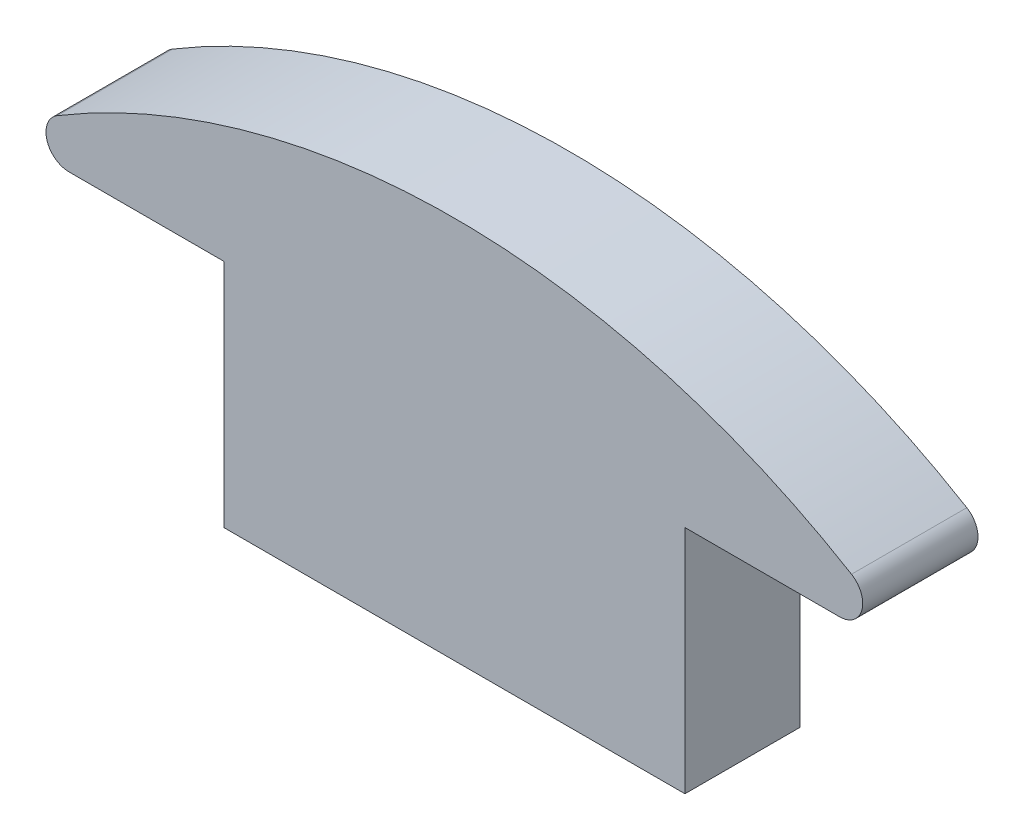
SolidWorks part; units mm, degrees
ref_plane "Ön Düzlem" through (0, 0, 0) normal (0, 0, 1) x (1, 0, 0)
ref_plane "Üst Düzlem" through (0, 0, 0) normal (0, 1, 0) x (1, 0, 0)
ref_plane "Sağ Düzlem" through (0, 0, 0) normal (1, 0, 0) x (0, 0, -1)
sketch "Sketch1" plane through (0, 0, 0) normal (0, 0, 1) x (1, 0, 0)
  line L0 (0, 1) -> (-0.671, 1)
  line L2 (0, 1) -> (0, 0)
  line L3 (0, 0) -> (2, 0)
  line L4 (2, 1) -> (2, 0)
  line L5 (2, 1) -> (2.671, 1)
  arc A0 (-0.7224, 1.1858) -> (2.7224, 1.1858) centre (1, -1.688) cw
  arc A1 (2.671, 1) -> (2.7224, 1.1858) centre (2.671, 1.1) ccw
  arc A2 (-0.671, 1) -> (-0.7224, 1.1858) centre (-0.671, 1.1) cw
  point P10 (3, 1)
  point P13 (-1, 1)
  dimension "D5" = 0.1
  dimension "D1" = 2
  dimension "D2" = 1
  dimension "D3" = 1
  dimension "D4" = 1
extrude "Boss-Extrude1" add sketch "Sketch1" along normal blind 0.5
